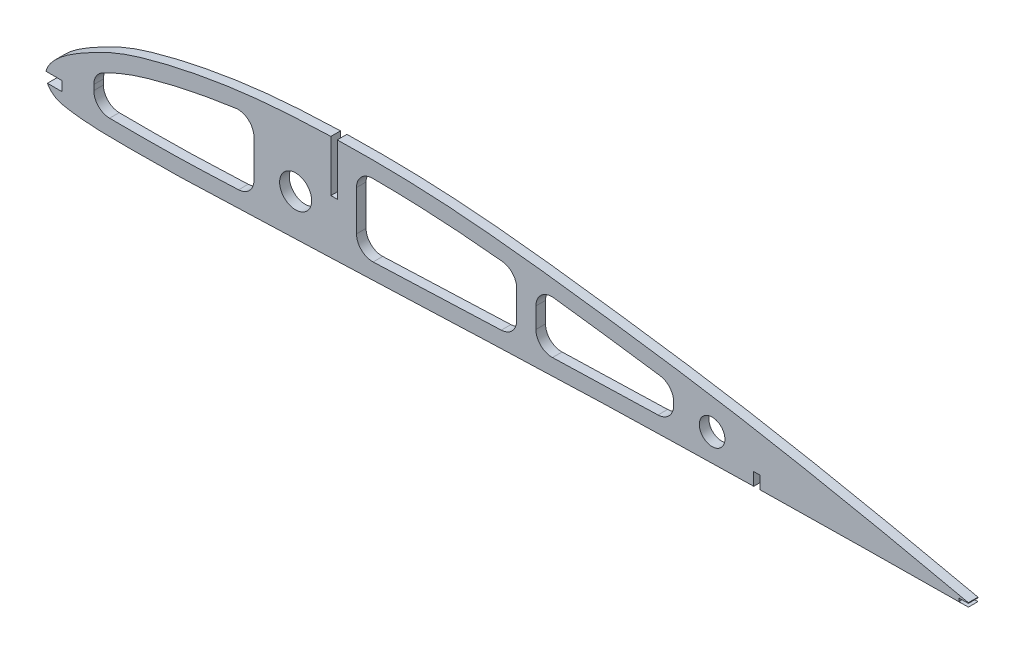
SolidWorks part; units mm, degrees
material "轻木"
ref_plane "前视基准面" through (0, 0, 0) normal (0, 0, 1) x (1, 0, 0)
ref_plane "上视基准面" through (0, 0, 0) normal (0, 1, 0) x (1, 0, 0)
ref_plane "右视基准面" through (0, 0, 0) normal (1, 0, 0) x (0, 0, -1)
other "Configuration Table"
curve "曲线1"
  spline degree 3 poles (300, 0.375, 0) (299.2857, 0.5355, 0) (297.8572, 0.8566, 0) (295.7147, 1.3378, 0) (293.5725, 1.8185, 0) (291.4302, 2.2982, 0) (289.2875, 2.7769, 0) (287.1442, 3.2543, 0) (285.001, 3.7299, 0) (282.8583, 4.2033, 0) (280.7163, 4.6744, 0) (278.5743, 5.1433, 0) (276.432, 5.6099, 0) (274.2889, 6.0741, 0) (272.145, 6.5358, 0) (269.2891, 7.1472, 0) (265.721, 7.9038, 0) (261.4399, 8.8, 0) (257.1573, 9.6847, 0) (252.8725, 10.5577, 0) (248.585, 11.4191, 0) (244.2942, 12.2686, 0) (240.0067, 13.1048, 0) (235.7231, 13.9276, 0) (231.4437, 14.735, 0) (227.1623, 15.5265, 0) (222.8779, 16.3002, 0) (218.5899, 17.0545, 0) (214.2976, 17.7876, 0) (210.0082, 18.4964, 0) (205.7223, 19.1793, 0) (201.441, 19.8388, 0) (197.1575, 20.4787, 0) (192.8717, 21.1016, 0) (188.5834, 21.71, 0) (184.2928, 22.3067, 0) (180.0042, 22.8936, 0) (175.7188, 23.4732, 0) (171.4371, 24.0431, 0) (167.1545, 24.6013, 0) (162.8704, 25.1452, 0) (158.5838, 25.6724, 0) (154.2938, 26.1804, 0) (150.0066, 26.6658, 0) (145.7226, 27.1265, 0) (141.4425, 27.5584, 0) (137.1601, 27.958, 0) (132.875, 28.3213, 0) (128.5869, 28.6439, 0) (124.2953, 28.9218, 0) (120.0053, 29.1506, 0) (115.7177, 29.3264, 0) (111.4337, 29.4514, 0) (107.1488, 29.5275, 0) (102.863, 29.5565, 0) (98.5762, 29.5401, 0) (94.2882, 29.4801, 0) (89.9957, 29.378, 0) (85.6999, 29.236, 0) (81.4026, 29.047, 0) (77.1093, 28.8043, 0) (72.8211, 28.5008, 0) (68.5389, 28.1296, 0) (64.264, 27.6835, 0) (60.7007, 27.2426, 0) (57.8461, 26.8442, 0) (55.696, 26.5216, 0) (53.5496, 26.1773, 0) (51.4067, 25.8115, 0) (49.2673, 25.4247, 0) (47.1314, 25.0171, 0) (44.9882, 24.5868, 0) (42.838, 24.1341, 0) (40.6818, 23.6568, 0) (38.5315, 23.1552, 0) (36.3875, 22.6273, 0) (34.2503, 22.0712, 0) (32.1202, 21.4847, 0) (30.3423, 20.9664, 0) (28.9132, 20.5311, 0) (27.8303, 20.1897, 0) (26.7518, 19.8362, 0) (25.6784, 19.4687, 0) (24.6112, 19.0858, 0) (23.551, 18.6856, 0) (22.4821, 18.2598, 0) (21.4059, 17.8057, 0) (20.3222, 17.3242, 0) (19.2465, 16.8243, 0) (18.1774, 16.3076, 0) (17.1139, 15.7762, 0) (16.0546, 15.2317, 0) (14.9819, 14.6674, 0) (13.8954, 14.0851, 0) (12.7977, 13.4827, 0) (11.7087, 12.8677, 0) (10.6313, 12.2387, 0) (9.5687, 11.5942, 0) (8.5237, 10.9329, 0) (7.6518, 10.3543, 0) (6.9458, 9.8665, 0) (6.3985, 9.4746, 0) (5.8573, 9.0705, 0) (5.3218, 8.651, 0) (4.7913, 8.2128, 0) (4.2653, 7.7527, 0) (3.6165, 7.1497, 0) (2.8604, 6.3846, 0) (2.0362, 5.4343, 0) (1.2959, 4.4252, 0) (0.6772, 3.3675, 0) (0.2189, 2.2697, 0) (-0.0383, 1.1392, 0) (-0.0456, 0.0749, 0) (0.1619, -0.885, 0) (0.4986, -1.7375, 0) (0.9635, -2.5517, 0) (1.5376, -3.3119, 0) (2.2026, -4.0019, 0) (2.94, -4.6051, 0) (3.6355, -5.044, 0) (4.2555, -5.3464, 0) (4.779, -5.5548, 0) (5.3118, -5.728, 0) (5.8521, -5.8723, 0) (6.398, -5.9938, 0) (6.9478, -6.0987, 0) (7.671, -6.2224, 0) (8.5669, -6.3647, 0) (9.636, -6.5177, 0) (10.7063, -6.6545, 0) (11.7778, -6.7754, 0) (12.8506, -6.8809, 0) (13.9246, -6.9713, 0) (14.9978, -7.047, 0) (16.0697, -7.1082, 0) (17.1403, -7.1566, 0) (18.2115, -7.1941, 0) (19.2831, -7.2222, 0) (20.3552, -7.2427, 0) (21.4275, -7.2573, 0) (22.4998, -7.2676, 0) (23.5718, -7.2752, 0) (24.6434, -7.2803, 0) (25.7147, -7.2832, 0) (26.7859, -7.2843, 0) (27.8572, -7.2839, 0) (28.9285, -7.2822, 0) (30.3573, -7.2788, 0) (32.1433, -7.2727, 0) (34.2864, -7.2613, 0) (36.4292, -7.2444, 0) (38.5718, -7.2208, 0) (40.7144, -7.1891, 0) (42.8572, -7.148, 0) (45.0005, -7.0962, 0) (47.1439, -7.0325, 0) (49.2871, -6.9587, 0) (51.4297, -6.8772, 0) (53.572, -6.7902, 0) (55.7143, -6.6999, 0) (57.857, -6.6086, 0) (60.7142, -6.4884, 0) (64.2858, -6.3465, 0) (68.5714, -6.1868, 0) (72.8565, -6.0353, 0) (77.1416, -5.8893, 0) (81.427, -5.7463, 0) (85.7132, -5.6038, 0) (90.0001, -5.4593, 0) (94.287, -5.3101, 0) (98.5731, -5.1566, 0) (102.8583, -4.9992, 0) (107.1431, -4.8383, 0) (111.4281, -4.6742, 0) (115.7138, -4.5074, 0) (120.0001, -4.3383, 0) (124.2865, -4.1673, 0) (128.5722, -3.9953, 0) (132.8572, -3.8233, 0) (137.142, -3.6525, 0) (141.4271, -3.4838, 0) (145.7131, -3.3181, 0) (149.9996, -3.1567, 0) (154.286, -3.0004, 0) (158.5714, -2.8495, 0) (162.8564, -2.7043, 0) (167.1412, -2.5651, 0) (171.4266, -2.4321, 0) (175.7128, -2.3056, 0) (179.9996, -2.1858, 0) (184.2862, -2.0731, 0) (188.5719, -1.9664, 0) (192.857, -1.8646, 0) (197.1419, -1.7668, 0) (201.4272, -1.6719, 0) (205.7132, -1.5788, 0) (209.9999, -1.4865, 0) (214.2864, -1.3941, 0) (218.5722, -1.3027, 0) (222.8572, -1.2136, 0) (227.142, -1.128, 0) (231.4272, -1.0471, 0) (235.7132, -0.9723, 0) (239.9998, -0.9046, 0) (244.2864, -0.8454, 0) (248.5722, -0.7928, 0) (252.8573, -0.7451, 0) (257.1422, -0.7003, 0) (261.4274, -0.6568, 0) (265.7134, -0.6127, 0) (269.2855, -0.574, 0) (272.1433, -0.5408, 0) (274.2862, -0.5157, 0) (276.4287, -0.4908, 0) (278.5712, -0.4671, 0) (280.7137, -0.4452, 0) (282.8567, -0.4258, 0) (285, -0.4096, 0) (287.1432, -0.3973, 0) (289.2862, -0.3884, 0) (291.4287, -0.3824, 0) (293.5711, -0.3786, 0) (295.7137, -0.3765, 0) (297.8567, -0.3754, 0) (299.2855, -0.3751, 0) (300, -0.375, 0) knots 0 0 0 0 0.003574 0.007146 0.010718 0.01429 0.017862 0.021434 0.025008 0.028577 0.032145 0.035713 0.03928 0.042847 0.046415 0.049985 0.057103 0.064219 0.071333 0.078448 0.085563 0.092679 0.099797 0.106885 0.11397 0.121053 0.128137 0.13522 0.142305 0.149391 0.15644 0.163488 0.170534 0.17758 0.184627 0.191675 0.198725 0.205755 0.212782 0.219809 0.226834 0.233861 0.240889 0.24792 0.254921 0.26192 0.268917 0.275914 0.28291 0.289907 0.296905 0.303879 0.310852 0.317824 0.324796 0.331771 0.338748 0.345728 0.352728 0.359727 0.366723 0.373717 0.380709 0.387701 0.394695 0.398233 0.40177 0.405307 0.408843 0.41238 0.415918 0.419457 0.42305 0.426643 0.430235 0.433828 0.43742 0.441014 0.444611 0.446459 0.448306 0.450153 0.451999 0.453844 0.455687 0.45753 0.459459 0.461388 0.463318 0.465249 0.467183 0.469121 0.471062 0.4731 0.475138 0.477173 0.479204 0.481227 0.483239 0.48524 0.486334 0.487428 0.488525 0.48963 0.490748 0.491883 0.493041 0.495071 0.497131 0.499176 0.501171 0.503098 0.50496 0.506796 0.508242 0.509728 0.511253 0.512804 0.514366 0.515919 0.517444 0.518368 0.519283 0.520192 0.521101 0.522011 0.522922 0.523833 0.525592 0.527349 0.529104 0.530859 0.532612 0.534366 0.53612 0.537863 0.539607 0.54135 0.543094 0.544839 0.546584 0.548329 0.550073 0.551817 0.55356 0.555302 0.557045 0.558788 0.560532 0.564019 0.567506 0.570992 0.574478 0.577965 0.581452 0.584939 0.588429 0.591918 0.595406 0.598895 0.602383 0.605872 0.609363 0.616342 0.623319 0.630295 0.637271 0.644247 0.651224 0.658203 0.665183 0.672161 0.679137 0.686114 0.69309 0.700068 0.707048 0.714028 0.721006 0.727983 0.73496 0.741937 0.748915 0.755896 0.762874 0.769851 0.776826 0.783801 0.790777 0.797753 0.804732 0.811709 0.818683 0.825657 0.83263 0.839604 0.846578 0.853555 0.860532 0.867506 0.874479 0.881452 0.888424 0.895399 0.902375 0.90935 0.916324 0.923296 0.930267 0.937239 0.944213 0.951188 0.954676 0.958163 0.961649 0.965135 0.96862 0.972107 0.975595 0.979082 0.982569 0.986054 0.98954 0.993026 0.996512 1 1 1 1
curve "曲线2"
  spline degree 3 poles (299.6892, 0.0825, 0) (300.1498, -0.0478, 0) (299.7114, 0.1074, 0) (299.5104, 0.1872, 0) (299.2477, 0.2871, 0) (298.8504, 0.4413, 0) (298.294, 0.6613, 0) (297.5919, 0.9463, 0) (296.8903, 1.2362, 0) (296.0644, 1.581, 0) (295.1136, 1.9799, 0) (294.0373, 2.431, 0) (292.9597, 2.8788, 0) (291.7683, 3.3665, 0) (290.4608, 3.8877, 0) (289.0365, 4.4399, 0) (287.6073, 4.9796, 0) (286.0635, 5.5484, 0) (284.4048, 6.1444, 0) (282.6311, 6.7664, 0) (280.8534, 7.377, 0) (278.9651, 8.0149, 0) (276.9667, 8.6805, 0) (274.8582, 9.373, 0) (272.7471, 10.0574, 0) (270.5382, 10.7652, 0) (268.2318, 11.4959, 0) (265.8278, 12.2485, 0) (263.4214, 12.9932, 0) (260.9293, 13.7558, 0) (258.3517, 14.5354, 0) (255.6885, 15.3308, 0) (253.0225, 16.1168, 0) (250.2835, 16.9138, 0) (247.4714, 17.7205, 0) (244.5864, 18.536, 0) (241.6982, 19.3402, 0) (238.749, 20.1489, 0) (235.7391, 20.9612, 0) (232.6684, 21.7757, 0) (229.594, 22.5763, 0) (226.4711, 23.374, 0) (223.2997, 24.1675, 0) (220.08, 24.9553, 0) (216.8561, 25.726, 0) (213.5945, 26.4871, 0) (210.2953, 27.2373, 0) (206.9588, 27.975, 0) (203.6178, 28.6919, 0) (200.2497, 29.3918, 0) (196.8549, 30.0732, 0) (193.4336, 30.7349, 0) (190.0077, 31.3718, 0) (186.5618, 31.9862, 0) (183.0963, 32.577, 0) (179.6117, 33.1436, 0) (176.1229, 33.6833, 0) (172.6234, 34.197, 0) (169.1136, 34.6844, 0) (165.5943, 35.1447, 0) (162.0713, 35.5767, 0) (158.5465, 35.9798, 0) (155.0205, 36.3535, 0) (151.4939, 36.6979, 0) (147.9646, 37.0129, 0) (144.4431, 37.2978, 0) (140.9302, 37.5529, 0) (137.4264, 37.7777, 0) (133.9208, 37.9727, 0) (130.4332, 38.1365, 0) (126.9642, 38.269, 0) (123.5147, 38.3706, 0) (120.0643, 38.4412, 0) (116.6408, 38.4803, 0) (113.2449, 38.4881, 0) (109.8772, 38.4649, 0) (106.5099, 38.4098, 0) (103.1795, 38.3231, 0) (99.8867, 38.2053, 0) (96.6323, 38.0567, 0) (93.3796, 37.8749, 0) (90.1728, 37.6618, 0) (87.0127, 37.4182, 0) (83.9, 37.1447, 0) (80.7905, 36.8368, 0) (77.7347, 36.4989, 0) (74.7332, 36.1323, 0) (71.7867, 35.7377, 0) (68.8452, 35.3075, 0) (65.9638, 34.8492, 0) (63.1431, 34.3642, 0) (60.3838, 33.8535, 0) (57.6314, 33.3063, 0) (54.9457, 32.7337, 0) (52.327, 32.1376, 0) (49.7758, 31.5197, 0) (47.2337, 30.8655, 0) (44.763, 30.1905, 0) (42.364, 29.4973, 0) (40.0371, 28.7872, 0) (37.7217, 28.0406, 0) (35.4836, 27.2778, 0) (33.323, 26.5013, 0) (31.2399, 25.7132, 0) (29.1709, 24.8888, 0) (27.1829, 24.0541, 0) (25.2756, 23.212, 0) (23.4491, 22.3647, 0) (21.6401, 21.481, 0) (19.9159, 20.5922, 0) (18.2759, 19.7016, 0) (16.7198, 18.8121, 0) (15.1846, 17.8866, 0) (13.7354, 16.9627, 0) (12.3708, 16.045, 0) (11.0909, 15.1361, 0) (9.8373, 14.192, 0) (8.6721, 13.2572, 0) (7.5935, 12.336, 0) (6.5993, 11.4319, 0) (5.6356, 10.4933, 0) (4.7571, 9.5716, 0) (3.961, 8.6731, 0) (3.2484, 7.802, 0) (2.5791, 6.9017, 0) (2.0018, 6.0303, 0) (1.5119, 5.1928, 0) (1.098, 4.3932, 0) (0.723, 3.565, 0) (0.4148, 2.7772, 0) (0.1635, 2.0409, 0) (-0.0076, 1.362, 0) (-0.0857, 0.6761, 0) (-0.0312, 0.0318, 0) (0.1575, -0.5446, 0) (0.4284, -1.0495, 0) (0.7766, -1.5095, 0) (1.2499, -1.9767, 0) (1.8739, -2.4002, 0) (2.6419, -2.7457, 0) (3.4475, -3.0028, 0) (4.3968, -3.243, 0) (5.4726, -3.4987, 0) (6.6732, -3.7581, 0) (7.8724, -3.9885, 0) (9.2039, -4.2095, 0) (10.6736, -4.4054, 0) (12.2821, -4.571, 0) (13.8972, -4.6995, 0) (15.6445, -4.8094, 0) (17.5211, -4.9053, 0) (19.5261, -4.9826, 0) (21.5305, -5.0368, 0) (23.661, -5.0721, 0) (25.9181, -5.0854, 0) (28.3014, -5.0749, 0) (30.6852, -5.0437, 0) (33.1885, -4.993, 0) (35.8107, -4.9237, 0) (38.5514, -4.8343, 0) (41.2914, -4.7299, 0) (44.1429, -4.6075, 0) (47.1057, -4.467, 0) (50.1792, -4.3077, 0) (53.2522, -4.1367, 0) (56.4269, -3.9498, 0) (59.7026, -3.7473, 0) (63.0791, -3.5293, 0) (66.4551, -3.3033, 0) (69.9209, -3.0645, 0) (73.4761, -2.8134, 0) (77.1202, -2.5502, 0) (80.764, -2.2824, 0) (84.4846, -2.0051, 0) (88.2815, -1.7191, 0) (92.1543, -1.4245, 0) (96.027, -1.128, 0) (99.9621, -0.8252, 0) (103.9592, -0.5167, 0) (108.0179, -0.2032, 0) (112.0767, 0.1098, 0) (116.1823, 0.4251, 0) (120.3344, 0.742, 0) (124.5324, 1.0596, 0) (128.7308, 1.3739, 0) (132.9595, 1.6861, 0) (137.2181, 1.9957, 0) (141.506, 2.3018, 0) (145.7945, 2.6016, 0) (150.096, 2.8954, 0) (154.41, 3.1825, 0) (158.7362, 3.4618, 0) (163.063, 3.7316, 0) (167.3848, 3.9907, 0) (171.7011, 4.2382, 0) (176.0115, 4.4733, 0) (180.3226, 4.6957, 0) (184.6083, 4.9033, 0) (188.8679, 5.0957, 0) (193.1011, 5.2721, 0) (197.335, 5.4325, 0) (201.5222, 5.5742, 0) (205.6623, 5.6969, 0) (209.7546, 5.8004, 0) (213.8473, 5.8854, 0) (217.8716, 5.9498, 0) (221.8268, 5.9942, 0) (225.7124, 6.0188, 0) (229.598, 6.0233, 0) (233.3935, 6.0071, 0) (237.0983, 5.971, 0) (240.7119, 5.9157, 0) (244.325, 5.8393, 0) (247.8275, 5.7436, 0) (251.2186, 5.6301, 0) (254.498, 5.5, 0) (257.7765, 5.3484, 0) (260.9253, 5.1809, 0) (263.9441, 4.9996, 0) (266.8324, 4.8058, 0) (269.7191, 4.5899, 0) (272.4587, 4.362, 0) (275.0509, 4.1249, 0) (277.4951, 3.8799, 0) (279.9368, 3.6105, 0) (282.2113, 3.3338, 0) (284.3185, 3.0537, 0) (286.2585, 2.7745, 0) (288.195, 2.4723, 0) (289.9467, 2.1761, 0) (291.5141, 1.8919, 0) (292.8979, 1.6262, 0) (294.2788, 1.3456, 0) (295.4709, 1.0894, 0) (296.4751, 0.8638, 0) (297.2928, 0.6738, 0) (298.1076, 0.4784, 0) (298.7442, 0.3204, 0) (299.1896, 0.208, 0) (299.4728, 0.1348, 0) (299.6892, 0.0825, 0) (300.1498, -0.0478, 0) (299.7114, 0.1074, 0) knots -0.001345 -0.000897 -0.000449 0 0.000432 0.000863 0.001295 0.001726 0.002951 0.004176 0.0054 0.006625 0.008509 0.010392 0.012274 0.014158 0.016623 0.019088 0.021553 0.024019 0.027053 0.030085 0.033118 0.036152 0.039734 0.043315 0.046896 0.050478 0.054544 0.058608 0.062672 0.066738 0.071224 0.075709 0.080193 0.084679 0.089518 0.094356 0.099193 0.104032 0.10916 0.114286 0.119411 0.124539 0.129889 0.135237 0.140585 0.145936 0.151451 0.156964 0.162478 0.167993 0.173617 0.17924 0.184862 0.190486 0.196184 0.20188 0.207576 0.213274 0.219003 0.22473 0.230457 0.236185 0.241905 0.247622 0.253339 0.259058 0.264725 0.270389 0.276054 0.281721 0.287291 0.29286 0.298428 0.303998 0.309434 0.314867 0.320301 0.325737 0.330995 0.336251 0.341507 0.346766 0.351809 0.356851 0.361892 0.366936 0.371734 0.37653 0.381327 0.386125 0.390654 0.395182 0.399709 0.404238 0.408475 0.41271 0.416945 0.421182 0.425109 0.429034 0.432959 0.436885 0.44048 0.444073 0.447666 0.451261 0.454511 0.457759 0.461007 0.464256 0.467149 0.470041 0.472933 0.475826 0.47836 0.480893 0.483425 0.485956 0.488123 0.490291 0.49246 0.494634 0.496453 0.49827 0.500081 0.501882 0.503328 0.504776 0.506239 0.507727 0.50887 0.510003 0.51111 0.512198 0.513104 0.514027 0.514959 0.515886 0.517235 0.518584 0.51995 0.521324 0.523324 0.525303 0.52727 0.529235 0.531836 0.534446 0.537062 0.539679 0.542921 0.546158 0.549393 0.552628 0.556473 0.560319 0.564166 0.568014 0.57244 0.576864 0.581288 0.585714 0.590681 0.595647 0.600613 0.605581 0.611042 0.616501 0.62196 0.627422 0.633319 0.639214 0.645109 0.651006 0.657275 0.663542 0.669809 0.676078 0.682648 0.689216 0.695784 0.702355 0.70915 0.715943 0.722736 0.729531 0.73647 0.743406 0.750342 0.757281 0.764278 0.771273 0.778268 0.785265 0.792232 0.799197 0.806162 0.81313 0.819969 0.826805 0.833641 0.840479 0.847087 0.853692 0.860297 0.866904 0.873175 0.879445 0.885714 0.891986 0.897819 0.90365 0.909481 0.915314 0.920611 0.925907 0.931202 0.936499 0.941172 0.945842 0.950513 0.955185 0.95915 0.963114 0.967077 0.971042 0.974206 0.977368 0.98053 0.983693 0.985968 0.988241 0.990515 0.992789 0.994144 0.995498 0.996852 0.998206 0.998655 0.999103 0.999551 1 1.000432 1.000863 1.001295 periodic
sketch "草图1" plane through (0, 0, 0) normal (0, 0, 1) x (1, 0, 0)
  line L1 (290, 2.6177) -> (290, -0.3866)
  line L2 (289, 1.8162) -> (289, 0.6101)
  line L3 (0, 0) -> (0, 30) construction
  line L4 (-6, -1.5) -> (6, -1.5)
  line L5 (-6, -1.5) -> (-6, 1.5)
  line L6 (-6, 1.5) -> (6, 1.5)
  line L7 (6, -1.5) -> (6, 1.5)
  line L8 (-6, -1.5) -> (6, 1.5) construction
  line L9 (-6, 1.5) -> (6, -1.5) construction
  line L10 (-1000, 0) -> (49000, 0) construction
  line L11 (90, 29.3715) -> (92, 29.3715)
  line L12 (90, 29.3715) -> (90, 12.3715)
  line L13 (90, 12.3715) -> (92, 12.3715)
  line L14 (92, 29.3715) -> (92, 12.3715)
  line L16 (222, -1.2317) -> (224, -1.2317)
  line L17 (222, -1.2317) -> (222, 3.7683)
  line L18 (222, 3.7683) -> (224, 3.7683)
  line L19 (224, -1.2317) -> (224, 3.7683)
  line L20 (289, 0.6101) -> (286, 0.6101)
  line L21 (289, 0.6101) -> (289, 1.6101)
  line L22 (289, 1.6101) -> (286, 1.6101)
  line L23 (286, 0.6101) -> (286, 1.6101)
  circle A0 centre (79, 8) radius 5
  circle A1 centre (209, 8) radius 4
  spline S0 degree 3 poles (1772.1833, 2527.0993) (871.6721, -135.2205) (584.8189, -63.6019) (295.7147, 1.3378) (293.5725, 1.8185) (291.4302, 2.2982) (289.2875, 2.7769) (287.1442, 3.2543) (285.001, 3.7299) (282.8583, 4.2033) (280.7163, 4.6744) (278.5743, 5.1433) (276.432, 5.6099) (274.2889, 6.0741) (272.145, 6.5358) (269.2891, 7.1472) (265.721, 7.9038) (261.4399, 8.8) (257.1573, 9.6847) (252.8725, 10.5577) (248.585, 11.4191) (244.2942, 12.2686) (240.0067, 13.1048) (234.2978, 14.2013) (228.5907, 15.2685) (222.8779, 16.3002) (218.5899, 17.0545) (214.2976, 17.7876) (210.0082, 18.4964) (205.7223, 19.1793) (201.441, 19.8388) (197.1575, 20.4787) (192.8717, 21.1016) (188.5834, 21.71) (184.2928, 22.3067) (180.0042, 22.8936) (175.7188, 23.4732) (171.4371, 24.0431) (167.1545, 24.6013) (162.8704, 25.1452) (158.5838, 25.6724) (154.2938, 26.1804) (150.0066, 26.6658) (145.7226, 27.1265) (141.4425, 27.5584) (137.1601, 27.958) (132.875, 28.3213) (128.5869, 28.6439) (124.2953, 28.9218) (120.0053, 29.1506) (115.7177, 29.3264) (111.4337, 29.4514) (107.1488, 29.5275) (102.863, 29.5565) (98.5762, 29.5401) (94.2882, 29.4801) (89.9957, 29.378) (85.6999, 29.236) (81.4026, 29.047) (77.1093, 28.8043) (72.8211, 28.5008) (68.5389, 28.1296) (64.264, 27.6835) (60.7007, 27.2426) (57.1284, 26.744) (53.5478, 26.188) (49.9791, 25.5605) (47.1314, 25.0171) (44.9882, 24.5868) (42.838, 24.1341) (40.6818, 23.6568) (38.5315, 23.1552) (36.3875, 22.6273) (34.2503, 22.0712) (32.1202, 21.4847) (30.3423, 20.9664) (28.9132, 20.5311) (27.8303, 20.1897) (26.7518, 19.8362) (25.6784, 19.4687) (24.6112, 19.0858) (23.551, 18.6856) (22.4821, 18.2598) (21.4059, 17.8057) (20.3222, 17.3242) (19.2465, 16.8243) (18.1774, 16.3076) (17.1139, 15.7762) (16.0546, 15.2317) (14.9819, 14.6674) (13.8954, 14.0851) (12.7977, 13.4827) (11.7087, 12.8677) (10.6313, 12.2387) (9.5687, 11.5942) (8.5237, 10.9329) (7.6518, 10.3543) (6.9458, 9.8665) (6.3985, 9.4746) (5.8573, 9.0705) (5.3218, 8.651) (4.7913, 8.2128) (4.2653, 7.7527) (3.6165, 7.1497) (2.8604, 6.3846) (2.0362, 5.4343) (1.2959, 4.4252) (0.6772, 3.3675) (0.2189, 2.2697) (-0.0383, 1.1392) (-0.0456, 0.0749) (0.1619, -0.885) (0.4986, -1.7375) (0.9635, -2.5517) (1.5376, -3.3119) (2.2026, -4.0019) (2.94, -4.6051) (3.6355, -5.044) (4.2555, -5.3464) (4.779, -5.5548) (5.3118, -5.728) (5.8521, -5.8723) (6.398, -5.9938) (6.9478, -6.0987) (7.671, -6.2224) (8.5669, -6.3647) (9.9918, -6.5686) (11.4199, -6.7402) (12.8506, -6.8809) (13.9246, -6.9713) (14.9978, -7.047) (16.0697, -7.1082) (17.1403, -7.1566) (18.2115, -7.1941) (19.2831, -7.2222) (20.3552, -7.2427) (21.4275, -7.2573) (22.4998, -7.2676) (23.5718, -7.2752) (24.6434, -7.2803) (25.7147, -7.2832) (27.143, -7.2847) (28.5715, -7.283) (30.3573, -7.2788) (32.1433, -7.2727) (34.2864, -7.2613) (36.4292, -7.2444) (38.5718, -7.2208) (40.7144, -7.1891) (42.8572, -7.148) (45.0005, -7.0962) (47.1439, -7.0325) (49.2871, -6.9587) (51.4297, -6.8772) (54.2862, -6.7612) (57.1429, -6.6386) (60.7142, -6.4884) (64.2858, -6.3465) (69.9995, -6.1336) (75.7132, -5.9369) (81.427, -5.7463) (85.7132, -5.6038) (90.0001, -5.4593) (94.287, -5.3101) (98.5731, -5.1566) (102.8583, -4.9992) (108.5717, -4.7846) (114.2856, -4.5638) (120.0001, -4.3383) (124.2865, -4.1673) (128.5722, -3.9953) (132.8572, -3.8233) (137.142, -3.6525) (141.4271, -3.4838) (145.7131, -3.3181) (149.9996, -3.1567) (154.286, -3.0004) (158.5714, -2.8495) (164.2846, -2.656) (171.4272, -2.4288) (179.9991, -2.1823) (187.1429, -2.0003) (192.857, -1.8646) (197.1419, -1.7668) (201.4272, -1.6719) (205.7132, -1.5788) (209.9999, -1.4865) (214.2864, -1.3941) (218.5722, -1.3027) (222.8572, -1.2136) (227.142, -1.128) (231.4272, -1.0471) (235.7132, -0.9723) (239.9998, -0.9046) (244.2864, -0.8454) (248.5722, -0.7928) (252.8573, -0.7451) (258.5708, -0.6854) (264.285, -0.6282) (269.2855, -0.574) (272.1433, -0.5408) (274.2862, -0.5157) (276.4287, -0.4908) (278.5712, -0.4671) (280.7137, -0.4452) (282.8567, -0.4258) (285, -0.4096) (287.1432, -0.3973) (289.2862, -0.3884) (291.4287, -0.3824) (293.5711, -0.3786) (295.7137, -0.3765) (521.6922, -0.2702) (746.959, -9.4705) (970.7683, 2878.2814) knots -1.435568 -1.435568 -1.435568 -1.435568 0.003574 0.007146 0.010718 0.01429 0.017862 0.021434 0.025008 0.028577 0.032145 0.035713 0.03928 0.042847 0.046415 0.049985 0.057103 0.064219 0.071333 0.078448 0.085563 0.092679 0.099797 0.106885 0.121053 0.128137 0.13522 0.142305 0.149391 0.15644 0.163488 0.170534 0.17758 0.184627 0.191675 0.198725 0.205755 0.212782 0.219809 0.226834 0.233861 0.240889 0.24792 0.254921 0.26192 0.268917 0.275914 0.28291 0.289907 0.296905 0.303879 0.310852 0.317824 0.324796 0.331771 0.338748 0.345728 0.352728 0.359727 0.366723 0.373717 0.380709 0.387701 0.394695 0.398233 0.405307 0.41238 0.415918 0.419457 0.42305 0.426643 0.430235 0.433828 0.43742 0.441014 0.444611 0.446459 0.448306 0.450153 0.451999 0.453844 0.455687 0.45753 0.459459 0.461388 0.463318 0.465249 0.467183 0.469121 0.471062 0.4731 0.475138 0.477173 0.479204 0.481227 0.483239 0.48524 0.486334 0.487428 0.488525 0.48963 0.490748 0.491883 0.493041 0.495071 0.497131 0.499176 0.501171 0.503098 0.50496 0.506796 0.508242 0.509728 0.511253 0.512804 0.514366 0.515919 0.517444 0.518368 0.519283 0.520192 0.521101 0.522011 0.522922 0.523833 0.525592 0.527349 0.530859 0.532612 0.534366 0.53612 0.537863 0.539607 0.54135 0.543094 0.544839 0.546584 0.548329 0.550073 0.551817 0.55356 0.555302 0.558788 0.560532 0.564019 0.567506 0.570992 0.574478 0.577965 0.581452 0.584939 0.588429 0.591918 0.595406 0.598895 0.605872 0.609363 0.616342 0.623319 0.637271 0.644247 0.651224 0.658203 0.665183 0.672161 0.679137 0.686114 0.700068 0.707048 0.714028 0.721006 0.727983 0.73496 0.741937 0.748915 0.755896 0.762874 0.769851 0.776826 0.790777 0.804732 0.818683 0.825657 0.83263 0.839604 0.846578 0.853555 0.860532 0.867506 0.874479 0.881452 0.888424 0.895399 0.902375 0.90935 0.916324 0.923296 0.930267 0.944213 0.951188 0.954676 0.958163 0.961649 0.965135 0.96862 0.972107 0.975595 0.979082 0.982569 0.986054 0.98954 0.993026 0.996512 2.092547 2.092547 2.092547 2.092547 only from (300, 0.375) to (300, -0.375) construction
  spline S1 degree 3 poles (290, 2.6177) (289.0482, 2.8302) (287.3817, 3.2016) (285.001, 3.7299) (282.8583, 4.2033) (280.7163, 4.6744) (278.5743, 5.1433) (276.432, 5.6099) (274.2889, 6.0741) (272.145, 6.5358) (269.2891, 7.1472) (265.721, 7.9038) (261.4399, 8.8) (257.1573, 9.6847) (252.8725, 10.5577) (248.585, 11.4191) (244.2942, 12.2686) (240.0067, 13.1048) (234.2978, 14.2013) (228.5907, 15.2685) (222.8779, 16.3002) (218.5899, 17.0545) (214.2976, 17.7876) (210.0082, 18.4964) (205.7223, 19.1793) (201.441, 19.8388) (197.1575, 20.4787) (192.8717, 21.1016) (188.5834, 21.71) (184.2928, 22.3067) (180.0042, 22.8936) (175.7188, 23.4732) (171.4371, 24.0431) (167.1545, 24.6013) (162.8704, 25.1452) (158.5838, 25.6724) (154.2938, 26.1804) (150.0066, 26.6658) (145.7226, 27.1265) (141.4425, 27.5584) (137.1601, 27.958) (132.875, 28.3213) (128.5869, 28.6439) (124.2953, 28.9218) (120.0053, 29.1506) (115.7177, 29.3264) (111.4337, 29.4514) (107.1488, 29.5275) (102.863, 29.5565) (98.5762, 29.5401) (94.2882, 29.4801) (89.9957, 29.378) (85.6999, 29.236) (81.4026, 29.047) (77.1093, 28.8043) (72.8211, 28.5008) (68.5389, 28.1296) (64.264, 27.6835) (60.7007, 27.2426) (57.1284, 26.744) (53.5478, 26.188) (49.9791, 25.5605) (47.1314, 25.0171) (44.9882, 24.5868) (42.838, 24.1341) (40.6818, 23.6568) (38.5315, 23.1552) (36.3875, 22.6273) (34.2503, 22.0712) (32.1202, 21.4847) (30.3423, 20.9664) (28.9132, 20.5311) (27.8303, 20.1897) (26.7518, 19.8362) (25.6784, 19.4687) (24.6112, 19.0858) (23.551, 18.6856) (22.4821, 18.2598) (21.4059, 17.8057) (20.3222, 17.3242) (19.2465, 16.8243) (18.1774, 16.3076) (17.1139, 15.7762) (16.0546, 15.2317) (14.9819, 14.6674) (13.8954, 14.0851) (12.7977, 13.4827) (11.7087, 12.8677) (10.6313, 12.2387) (9.5687, 11.5942) (8.5237, 10.9329) (7.6518, 10.3543) (6.9458, 9.8665) (6.3985, 9.4746) (5.8573, 9.0705) (5.3218, 8.651) (4.7913, 8.2128) (4.2653, 7.7527) (3.6165, 7.1497) (2.8604, 6.3846) (2.0362, 5.4343) (1.2959, 4.4252) (0.6772, 3.3675) (0.2189, 2.2697) (-0.0383, 1.1392) (-0.0456, 0.0749) (0.1619, -0.885) (0.4986, -1.7375) (0.9635, -2.5517) (1.5376, -3.3119) (2.2026, -4.0019) (2.94, -4.6051) (3.6355, -5.044) (4.2555, -5.3464) (4.779, -5.5548) (5.3118, -5.728) (5.8521, -5.8723) (6.398, -5.9938) (6.9478, -6.0987) (7.671, -6.2224) (8.5669, -6.3647) (9.9918, -6.5686) (11.4199, -6.7402) (12.8506, -6.8809) (13.9246, -6.9713) (14.9978, -7.047) (16.0697, -7.1082) (17.1403, -7.1566) (18.2115, -7.1941) (19.2831, -7.2222) (20.3552, -7.2427) (21.4275, -7.2573) (22.4998, -7.2676) (23.5718, -7.2752) (24.6434, -7.2803) (25.7147, -7.2832) (27.143, -7.2847) (28.5715, -7.283) (30.3573, -7.2788) (32.1433, -7.2727) (34.2864, -7.2613) (36.4292, -7.2444) (38.5718, -7.2208) (40.7144, -7.1891) (42.8572, -7.148) (45.0005, -7.0962) (47.1439, -7.0325) (49.2871, -6.9587) (51.4297, -6.8772) (54.2862, -6.7612) (57.1429, -6.6386) (60.7142, -6.4884) (64.2858, -6.3465) (69.9995, -6.1336) (75.7132, -5.9369) (81.427, -5.7463) (85.7132, -5.6038) (90.0001, -5.4593) (94.287, -5.3101) (98.5731, -5.1566) (102.8583, -4.9992) (108.5717, -4.7846) (114.2856, -4.5638) (120.0001, -4.3383) (124.2865, -4.1673) (128.5722, -3.9953) (132.8572, -3.8233) (137.142, -3.6525) (141.4271, -3.4838) (145.7131, -3.3181) (149.9996, -3.1567) (154.286, -3.0004) (158.5714, -2.8495) (164.2846, -2.656) (171.4272, -2.4288) (179.9991, -2.1823) (187.1429, -2.0003) (192.857, -1.8646) (197.1419, -1.7668) (201.4272, -1.6719) (205.7132, -1.5788) (209.9999, -1.4865) (214.2864, -1.3941) (218.5722, -1.3027) (222.8572, -1.2136) (227.142, -1.128) (231.4272, -1.0471) (235.7132, -0.9723) (239.9998, -0.9046) (244.2864, -0.8454) (248.5722, -0.7928) (252.8573, -0.7451) (258.5708, -0.6854) (264.285, -0.6282) (269.2855, -0.574) (272.1433, -0.5408) (274.2862, -0.5157) (276.4287, -0.4908) (278.5712, -0.4671) (280.7137, -0.4452) (282.8567, -0.4258) (285, -0.4096) (287.1432, -0.3973) (288.8099, -0.3904) (289.7621, -0.3873) (290, -0.3866) knots 0.016674 0.016674 0.016674 0.016674 0.021434 0.025008 0.028577 0.032145 0.035713 0.03928 0.042847 0.046415 0.049985 0.057103 0.064219 0.071333 0.078448 0.085563 0.092679 0.099797 0.106885 0.121053 0.128137 0.13522 0.142305 0.149391 0.15644 0.163488 0.170534 0.17758 0.184627 0.191675 0.198725 0.205755 0.212782 0.219809 0.226834 0.233861 0.240889 0.24792 0.254921 0.26192 0.268917 0.275914 0.28291 0.289907 0.296905 0.303879 0.310852 0.317824 0.324796 0.331771 0.338748 0.345728 0.352728 0.359727 0.366723 0.373717 0.380709 0.387701 0.394695 0.398233 0.405307 0.41238 0.415918 0.419457 0.42305 0.426643 0.430235 0.433828 0.43742 0.441014 0.444611 0.446459 0.448306 0.450153 0.451999 0.453844 0.455687 0.45753 0.459459 0.461388 0.463318 0.465249 0.467183 0.469121 0.471062 0.4731 0.475138 0.477173 0.479204 0.481227 0.483239 0.48524 0.486334 0.487428 0.488525 0.48963 0.490748 0.491883 0.493041 0.495071 0.497131 0.499176 0.501171 0.503098 0.50496 0.506796 0.508242 0.509728 0.511253 0.512804 0.514366 0.515919 0.517444 0.518368 0.519283 0.520192 0.521101 0.522011 0.522922 0.523833 0.525592 0.527349 0.530859 0.532612 0.534366 0.53612 0.537863 0.539607 0.54135 0.543094 0.544839 0.546584 0.548329 0.550073 0.551817 0.55356 0.555302 0.558788 0.560532 0.564019 0.567506 0.570992 0.574478 0.577965 0.581452 0.584939 0.588429 0.591918 0.595406 0.598895 0.605872 0.609363 0.616342 0.623319 0.637271 0.644247 0.651224 0.658203 0.665183 0.672161 0.679137 0.686114 0.700068 0.707048 0.714028 0.721006 0.727983 0.73496 0.741937 0.748915 0.755896 0.762874 0.769851 0.776826 0.790777 0.804732 0.818683 0.825657 0.83263 0.839604 0.846578 0.853555 0.860532 0.867506 0.874479 0.881452 0.888424 0.895399 0.902375 0.90935 0.916324 0.923296 0.930267 0.944213 0.951188 0.954676 0.958163 0.961649 0.965135 0.96862 0.972107 0.975595 0.979082 0.982569 0.98373 0.98373 0.98373 0.98373
  spline S2 degree 1 poles (289, 1.8162) (289, 0.6101) knots 0 0 1 1 construction
  spline S3 degree 3 poles (289, 1.8162) (276.9573, 4.5023) (258.8616, 8.3976) (234.6482, 13.1528) (216.4485, 16.4789) (198.1829, 19.3716) (179.8506, 21.9241) (161.5032, 24.3586) (143.1279, 26.4732) (124.7122, 28.0438) (106.2546, 28.676) (87.7718, 28.43) (72.4033, 27.5865) (60.1859, 26.2263) (51.081, 24.7981) (42.0339, 23.0001) (34.582, 21.1749) (28.6974, 19.4456) (24.362, 17.9834) (20.1748, 16.2079) (16.0789, 14.1399) (12.0403, 11.9468) (8.1401, 9.5604) (5.1537, 7.3164) (3.1001, 5.2006) (1.8138, 3.4707) (0.9689, 1.5796) (0.9059, -0.2656) (1.7459, -2.0716) (3.1431, -3.6011) (4.8543, -4.6194) (6.9276, -5.1056) (9.209, -5.4548) (12.22, -5.8429) (16.0201, -6.1427) (20.6095, -6.2611) (25.2315, -6.2869) (31.3974, -6.2803) (39.1073, -6.2407) (48.3368, -6.0221) (57.5799, -5.613) (66.8407, -5.2429) (76.0966, -4.9217) (88.436, -4.516) (103.8531, -3.9731) (122.3546, -3.2481) (140.8578, -2.4955) (159.3685, -1.8041) (177.8842, -1.2225) (196.4034, -0.7749) (214.9166, -0.3802) (233.434, 0.0126) (251.9612, 0.2567) (270.4719, 0.4292) (282.8248, 0.5874) (289, 0.6101) knots 0.017978 0.017978 0.017978 0.017978 0.078237 0.108366 0.138495 0.168624 0.198753 0.228882 0.259011 0.28914 0.319269 0.349398 0.379527 0.394592 0.409656 0.424721 0.439785 0.447318 0.45485 0.462382 0.469915 0.477447 0.484979 0.492511 0.496277 0.500044 0.50381 0.507576 0.511342 0.515108 0.518874 0.52264 0.526407 0.530173 0.537705 0.545237 0.552769 0.560302 0.575366 0.590431 0.605495 0.62056 0.635624 0.650689 0.680818 0.710947 0.741076 0.771205 0.801334 0.831463 0.861593 0.891722 0.921851 0.95198 0.982109 0.982109 0.982109 0.982109
  point P8 (0, 0)
  dimension "D9" = 10
  dimension "D10" = 8
  dimension "D1" = 290
  dimension "D2" = 1
  dimension "D3" = 12
  dimension "D4" = 3
  dimension "D5" = 30
  dimension "D6" = 2
  dimension "D7" = 17
  dimension "D8" = 90
  dimension "D11" = 130
  dimension "D12" = 11
  dimension "D13" = 8
  dimension "D14" = 5
  dimension "D15" = 2
  dimension "D16" = 130
  dimension "D17" = 1
  dimension "D18" = 3
extrude "凸台-拉伸1" add sketch "草图1" along normal blind 3 contours L2 S3 | S1 L1
sketch "草图3" plane through (0, 0, 0) normal (0, 0, 1) x (1, 0, 0)
  line L12 (16, 5.403) -> (16, 3.7496)
  line L13 (66, 16.1752) -> (66, 4.5297)
  line L14 (98, 18.5501) -> (98, 6.0145)
  line L15 (148, 16.344) -> (148, 7.5847)
  line L16 (154, 14.5377) -> (154, 8.1706)
  line L17 (197, 10.112) -> (197, 9.1173)
  line L18 (92, 28.4259) -> (92, 12.3715) construction
  arc A19 (197, 9.1173) -> (192.1175, 4.1186) centre (192, 9.1173) cw
  arc A20 (197, 10.112) -> (192.7141, 15.0608) centre (192, 10.112) ccw
  arc A21 (154, 8.1706) -> (159.172, 3.1736) centre (159, 8.1706) ccw
  arc A22 (154, 14.5377) -> (159.6086, 19.5005) centre (159, 14.5377) cw
  arc A23 (148, 7.5847) -> (143.1924, 2.5884) centre (143, 7.5847) cw
  arc A24 (148, 16.344) -> (143.5053, 21.3184) centre (143, 16.344) ccw
  arc A25 (98, 6.0145) -> (103.1854, 1.0179) centre (103, 6.0145) ccw
  arc A26 (98, 18.5501) -> (103.0112, 23.5501) centre (103, 18.5501) cw
  arc A27 (66, 16.1752) -> (60.3235, 21.1292) centre (61, 16.1752) ccw
  arc A28 (66, 4.5297) -> (61.2014, -0.4662) centre (61, 4.5297) cw
  arc A29 (16, 3.7496) -> (20.9267, -1.2499) centre (21, 3.7496) ccw
  arc A30 (16, 5.403) -> (18.6935, 9.8392) centre (21, 5.403) cw
  spline S4 degree 3 poles (1223.5899, -3807.8172) (41.0221, -18.1343) (3.5911, 4.1805) (6.0458, 0.6813) (6.0892, 0.6258) (6.1853, 0.517) (6.2378, 0.4636) (6.3432, 0.3675) (6.3951, 0.3256) (6.5408, 0.22) (6.6279, 0.171) (6.7674, 0.1131) (6.7979, 0.1013) (6.8795, 0.0726) (6.9285, 0.0566) (7.1004, 0.0051) (7.2482, -0.0334) (7.5161, -0.0939) (7.6131, -0.1145) (7.8217, -0.1566) (7.9344, -0.1783) (8.2795, -0.2424) (8.5214, -0.284) (9.0225, -0.365) (9.2817, -0.4044) (9.8121, -0.4817) (10.0842, -0.5199) (10.889, -0.6292) (11.4196, -0.6959) (12.4749, -0.8155) (13.0043, -0.8689) (14.6023, -1.0113) (15.6759, -1.0822) (17.8501, -1.1835) (18.9555, -1.2147) (21.203, -1.2568) (22.3422, -1.2684) (24.6314, -1.2817) (25.7846, -1.2836) (29.2463, -1.2839) (31.5645, -1.2776) (36.1788, -1.2497) (38.4772, -1.2258) (43.0659, -1.1434) (45.3578, -1.0858) (49.9421, -0.9354) (52.2436, -0.841) (56.8766, -0.6452) (59.208, -0.5461) (63.8664, -0.3594) (66.1973, -0.2702) (73.1841, -0.0163) (77.8342, 0.1367) (87.1208, 0.4464) (91.7586, 0.6052) (101.0358, 0.9364) (105.6732, 1.1088) (119.5909, 1.6442) (128.8734, 2.0262) (147.4638, 2.759) (156.7689, 3.1047) (170.7325, 3.5528) (175.3887, 3.6908) (184.6999, 3.9415) (189.3536, 4.0551) (198.6561, 4.2702) (203.3049, 4.372) (536.6269, 11.5362) (853.1308, 17.4667) (4030.1573, -1188.0537) knots -0.259948 -0.259948 -0.259948 -0.259948 0.003906 0.003906 0.007812 0.007812 0.011719 0.011719 0.015625 0.015625 0.023437 0.023437 0.025391 0.025391 0.027344 0.027344 0.03125 0.03125 0.033203 0.033203 0.035156 0.035156 0.039062 0.039062 0.042969 0.042969 0.046875 0.046875 0.054687 0.054687 0.0625 0.0625 0.078125 0.078125 0.09375 0.09375 0.109375 0.109375 0.125 0.125 0.15625 0.15625 0.1875 0.1875 0.21875 0.21875 0.25 0.25 0.28125 0.28125 0.3125 0.3125 0.375 0.375 0.4375 0.4375 0.5 0.5 0.625 0.625 0.75 0.75 0.8125 0.8125 0.875 0.875 0.9375 0.9375 5.35729 5.35729 5.35729 5.35729 only from (5.9323, 0.8564) to (221.8968, 4.7675)
  spline S8 degree 3 poles (1949.8235, 2245.1607) (1149.9303, -374.9257) (720.0438, -93.81) (255.5122, 3.9147) (247.3983, 5.5603) (235.2101, 7.9212) (231.1442, 8.6918) (223.0151, 10.1863) (218.9514, 10.9093) (210.8193, 12.2884) (206.7464, 12.946) (198.587, 14.2066) (194.5005, 14.8087) (186.309, 15.9748) (182.2038, 16.5396) (173.988, 17.6533) (169.883, 18.1998) (157.5748, 19.7777) (149.3774, 20.7488) (137.0956, 21.9495) (133.0067, 22.3058) (124.8388, 22.8919) (120.7603, 23.1184) (112.5893, 23.4319) (108.5002, 23.5206) (-271.0088, 25.7281) (-677.8185, -516.1368) (1511.4906, 2627.9376) knots -6.913793 -6.913793 -6.913793 -6.913793 0.125 0.125 0.25 0.25 0.3125 0.3125 0.375 0.375 0.4375 0.4375 0.5 0.5 0.5625 0.5625 0.625 0.625 0.75 0.75 0.8125 0.8125 0.875 0.875 0.9375 0.9375 6.670657 6.670657 6.670657 6.670657 only from (287.9115, -3.0638) to (92.122, 23.4274)
  spline S9 degree 3 poles (192.7141, 15.0608) (191.9446, 15.1718) (191.1748, 15.2821) (186.309, 15.9748) (182.2038, 16.5396) (173.988, 17.6533) (169.883, 18.1998) (163.7225, 18.9896) (161.6653, 19.2483) (159.6086, 19.5005) knots 0.488248 0.488248 0.488248 0.488248 0.5 0.5 0.5625 0.5625 0.625 0.625 0.656347 0.656347 0.656347 0.656347
  spline S11 degree 3 poles (183.5191, 1998.6141) (444.3406, -148.8158) (246.3269, 40.0107) (64.1587, 21.6485) (60.4651, 21.183) (53.1092, 20.0468) (49.4459, 19.3843) (42.1587, 17.8687) (38.5334, 17.0196) (33.149, 15.5462) (31.3629, 15.0224) (27.821, 13.8802) (26.0672, 13.2533) (22.6358, 11.8127) (20.9579, 11.0048) (17.648, 9.3036) (16.0082, 8.4228) (13.5937, 7.0224) (12.7968, 6.5418) (11.2302, 5.5376) (10.459, 5.016) (8.9706, 3.8992) (8.2535, 3.3022) (7.272, 2.3101) (6.9596, 1.9643) (6.5302, 1.4143) (6.3938, 1.2256) (6.2082, 0.9302) (6.1495, 0.8297) (6.069, 0.675) (6.0433, 0.6225) (6.0083, 0.5426) (5.9972, 0.5158) (5.9815, 0.4751) (5.9764, 0.4615) (5.9691, 0.441) (5.9667, 0.4341) (5.9633, 0.4238) (5.9621, 0.4203) (5.9605, 0.4151) (5.9599, 0.4133) (5.9286, 0.3128) (0.1534, -9.669) (975.7887, 1656.332) knots -0.51578 -0.51578 -0.51578 -0.51578 0.022329 0.022329 0.033494 0.033494 0.044659 0.044659 0.055823 0.055823 0.061406 0.061406 0.066988 0.066988 0.07257 0.07257 0.078153 0.078153 0.080944 0.080944 0.083735 0.083735 0.086526 0.086526 0.087922 0.087922 0.08862 0.08862 0.088968 0.088968 0.089143 0.089143 0.08923 0.08923 0.089274 0.089274 0.089296 0.089296 0.089306 0.089306 0.089312 0.089312 0.089622 0.089622 0.089622 0.089622 only from (90.1451, 23.3745) to (5.9578, 0.4064)
  spline S12 degree 3 poles (60.3235, 21.1292) (59.1433, 20.9681) (57.9644, 20.7967) (53.1092, 20.0468) (49.4459, 19.3843) (42.1587, 17.8687) (38.5334, 17.0196) (33.149, 15.5462) (31.3629, 15.0224) (27.821, 13.8802) (26.0672, 13.2533) (22.6358, 11.8127) (20.9579, 11.0048) (19.0996, 10.0497) (18.8964, 9.9447) (18.6935, 9.8392) knots 0.02992 0.02992 0.02992 0.02992 0.033494 0.033494 0.044659 0.044659 0.055823 0.055823 0.061406 0.061406 0.066988 0.066988 0.07257 0.07257 0.073256 0.073256 0.073256 0.073256
  spline S13 degree 3 poles (20.9267, -1.2499) (21.7742, -1.2623) (22.6289, -1.2701) (24.6314, -1.2817) (25.7846, -1.2836) (29.2463, -1.2839) (31.5645, -1.2776) (36.1788, -1.2497) (38.4772, -1.2258) (43.0659, -1.1434) (45.3578, -1.0858) (49.9421, -0.9354) (52.2436, -0.841) (56.7653, -0.6499) (58.984, -0.5556) (61.2014, -0.4662) knots 0.097665 0.097665 0.097665 0.097665 0.109375 0.109375 0.125 0.125 0.15625 0.15625 0.1875 0.1875 0.21875 0.21875 0.25 0.25 0.279748 0.279748 0.279748 0.279748
  spline S14 degree 3 poles (103.1854, 1.0179) (105.5609, 1.1061) (107.9364, 1.1959) (119.5909, 1.6442) (128.8734, 2.0262) (139.8429, 2.4586) (141.5175, 2.5239) (143.1924, 2.5884) knots 0.46799 0.46799 0.46799 0.46799 0.5 0.5 0.625 0.625 0.647516 0.647516 0.647516 0.647516
  spline S15 degree 3 poles (143.5053, 21.3184) (142.7333, 21.3969) (141.9614, 21.4738) (137.0956, 21.9495) (133.0067, 22.3058) (124.8388, 22.8919) (120.7603, 23.1184) (112.5893, 23.4319) (108.5002, 23.5206) (103.9422, 23.5472) (103.4767, 23.549) (103.0112, 23.5501) knots 0.738217 0.738217 0.738217 0.738217 0.75 0.75 0.8125 0.8125 0.875 0.875 0.9375 0.9375 0.944608 0.944608 0.944608 0.944608
  spline S16 degree 3 poles (159.172, 3.1736) (161.4737, 3.2528) (163.7757, 3.3295) (170.7325, 3.5528) (175.3887, 3.6908) (184.0702, 3.9245) (188.0947, 4.0241) (192.1175, 4.1186) knots 0.719086 0.719086 0.719086 0.719086 0.75 0.75 0.8125 0.8125 0.866547 0.866547 0.866547 0.866547
  dimension "D9" = 43
  dimension "D10" = 5
  dimension "D4" = 16
  dimension "D5" = 66
  dimension "D6" = 6
  dimension "D7" = 56
  dimension "D8" = 6
  dimension "D1" = 5
  dimension "D2" = 5
  dimension "D3" = 5
extrude "切除-拉伸2" cut sketch "草图3" along normal through all
